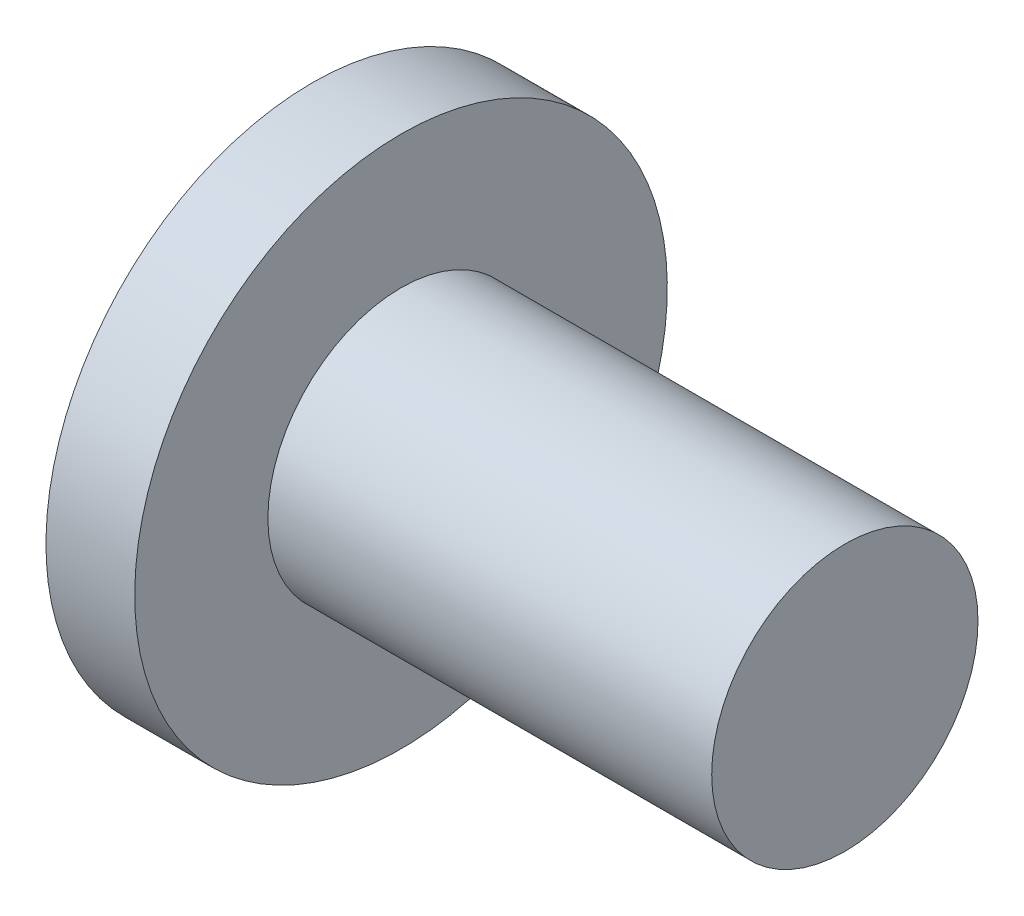
SolidWorks part; units mm, degrees
ref_plane "Front Plane" through (0, 0, 0) normal (0, 0, 1) x (1, 0, 0)
ref_plane "Top Plane" through (0, 0, 0) normal (0, 1, 0) x (1, 0, 0)
ref_plane "Right Plane" through (0, 0, 0) normal (1, 0, 0) x (0, 0, -1)
sketch "Sketch1" plane through (0, 0, 0) normal (0, 0, 1) x (1, 0, 0)
  line L0 (0, 0) -> (-12, 0)
  line L1 (-12, 0) -> (-12, 6)
  line L2 (-12, 6) -> (-10, 6)
  line L3 (-10, 6) -> (-10, 3)
  line L4 (-10, 3) -> (0, 3)
  line L5 (0, 3) -> (0, 0)
  dimension "D1" = 3
  dimension "D2" = 10
  dimension "D3" = 2
  dimension "D4" = 6
revolve "Revolve1" add sketch "Sketch1" angle 360 about L0
